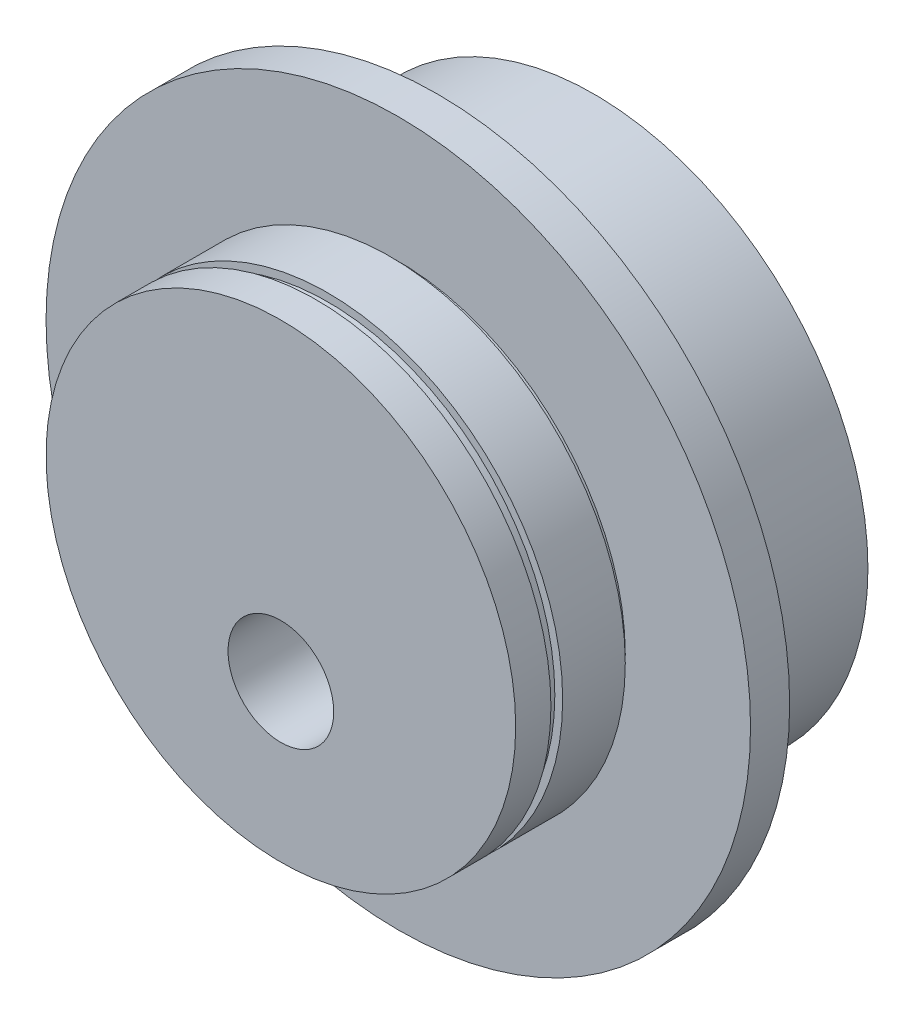
SolidWorks part; units mm, degrees
ref_plane "Front Plane" through (0, 0, 0) normal (0, 0, 1) x (1, 0, 0)
ref_plane "Top Plane" through (0, 0, 0) normal (0, 1, 0) x (1, 0, 0)
ref_plane "Right Plane" through (0, 0, 0) normal (1, 0, 0) x (0, 0, -1)
sketch "Sketch1" plane through (0, 0, 0) normal (0, 0, 1) x (1, 0, 0)
  circle A0 centre (0, 0) radius 44.45
  dimension "D1" = 88.9
extrude "Boss-Extrude1" add sketch "Sketch1" along normal blind 25.4
sketch "Sketch2" plane through (0, 0, 25.4) normal (0, 0, 1) x (1, 0, 0)
  circle A0 centre (0, 0) radius 36.83
  dimension "D1" = 73.66
extrude "Boss-Extrude2" add sketch "Sketch2" along normal blind 25.4
sketch "Sketch7" plane through (0, 0, 25.4) normal (0, 0, 1) x (1, 0, 0)
  circle A0 centre (0, 0) radius 38.1
  dimension "D1" = 76.2
extrude "Boss-Extrude3" add sketch "Sketch7" along normal blind 5.715
sketch "Sketch8" plane through (0, 0, 50.8) normal (0, 0, 1) x (1, 0, 0)
  circle A0 centre (0, 0) radius 38.1
  dimension "D1" = 76.2
extrude "Boss-Extrude4" add sketch "Sketch8" against normal blind 5.715
sketch "Sketch11" plane through (0, 0, 25.4) normal (0, 0, 1) x (1, 0, 0)
  circle A0 centre (0, 0) radius 38.1
extrude "Boss-Extrude6" add sketch "Sketch11" along normal blind 10.16 from offset 7.62
sketch "Sketch12" plane through (0, 0, 25.4) normal (0, 0, 1) x (1, 0, 0)
  circle A0 centre (0, 0) radius 57.15
extrude "Boss-Extrude7" add sketch "Sketch12" along normal blind 6.35
sketch "Sketch3" plane through (0, 0, 50.8) normal (0, 0, 1) x (1, 0, 0)
  circle A0 centre (0, -12.7) radius 8.5725
  dimension "D1" = 17.145
extrude "Cut-Extrude1" cut sketch "Sketch3" against normal through all both and the other way through all
